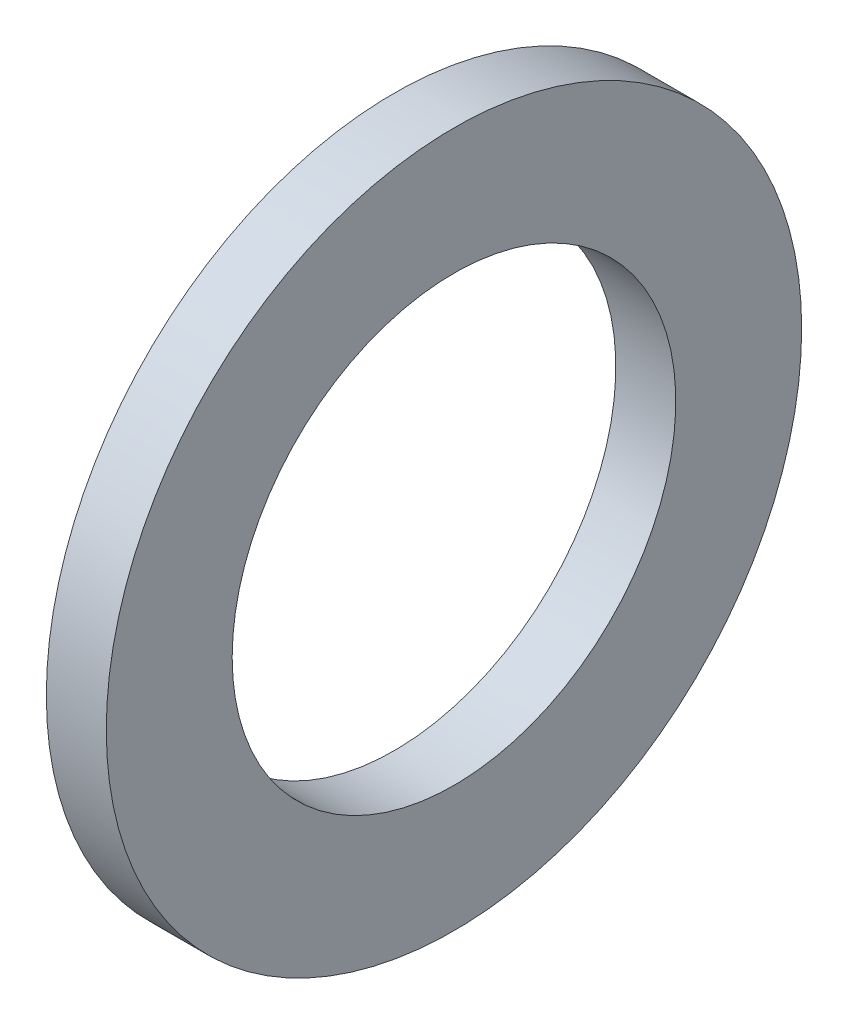
SolidWorks part; units mm, degrees
ref_plane "Plane1" through (0, 0, 0) normal (0, 0, 1) x (1, 0, 0)
ref_plane "Plane2" through (0, 0, 0) normal (0, 1, 0) x (1, 0, 0)
ref_plane "Plane3" through (0, 0, 0) normal (1, 0, 0) x (0, 0, -1)
sketch "Sketch1" plane through (0, 0, 0) normal (0, 0, 1) x (1, 0, 0)
  line L0 (-34.925, 0) -> (9.525, 0) construction
  line L1 (0, 18.5) -> (0, 29)
  line L2 (0, 29) -> (-5, 29)
  line L3 (-5, 29) -> (-5, 18.5)
  line L4 (-5, 18.5) -> (0, 18.5)
  dimension "Thickness" = 5
  dimension "Inside_dia" = 37
  dimension "Outside_dia" = 58
revolve "Base-Revolve" add sketch "Sketch1" angle 360 about L0
